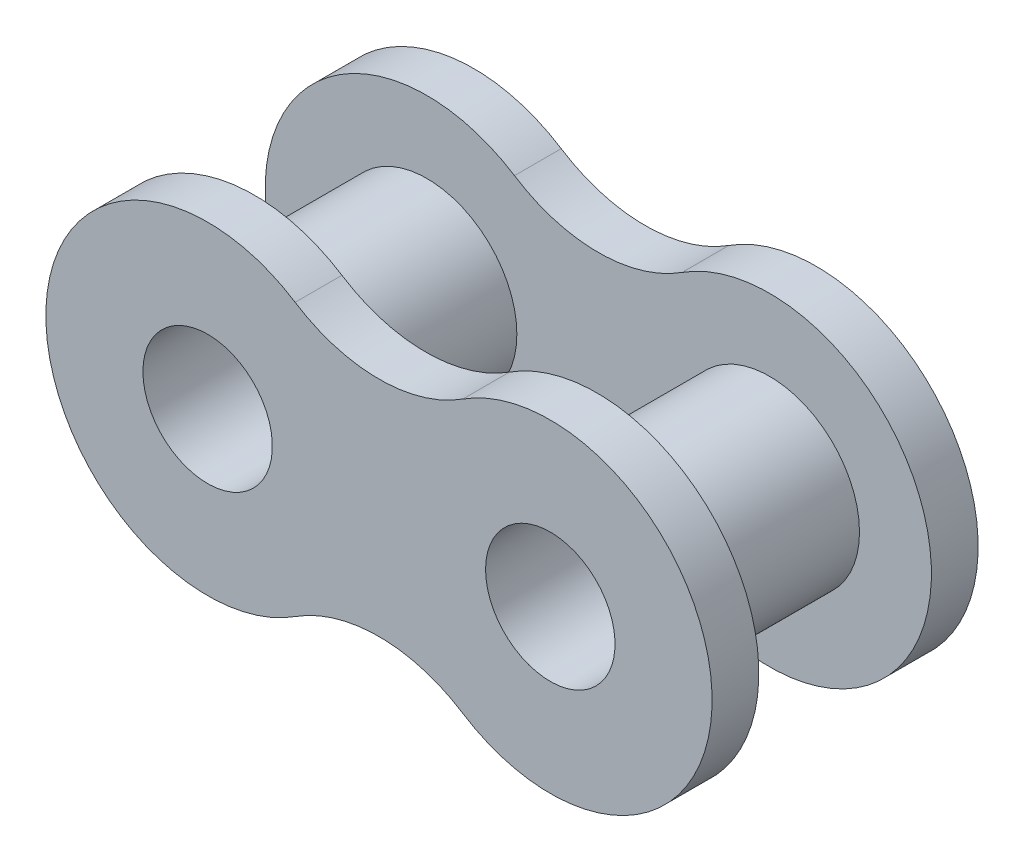
SolidWorks part; units mm, degrees
ref_plane "Alzado" through (0, 0, 0) normal (0, 0, 1) x (1, 0, 0)
ref_plane "Planta" through (0, 0, 0) normal (0, 1, 0) x (1, 0, 0)
ref_plane "Vista lateral" through (0, 0, 0) normal (1, 0, 0) x (0, 0, -1)
sketch "Sketch1" plane through (0, 0, 0) normal (0, 0, 1) x (1, 0, 0)
  line L0 (-9.265, 0) -> (9.265, 0) construction
  line L1 (0, 3.1) -> (0, -3.1) construction
  arc A0 (-2.3308, 3.7848) -> (-2.3308, -3.7848) centre (-4.765, 0) ccw
  arc A1 (-2.3308, 3.7848) -> (2.3308, 3.7848) centre (0, 7.409) ccw
  arc A2 (-2.3308, -3.7848) -> (2.3308, -3.7848) centre (0, -7.409) cw
  arc A3 (2.3308, 3.7848) -> (2.3308, -3.7848) centre (4.765, 0) cw
  point P4 (0, 0)
  point P10 (0, 0)
  dimension "D1" = 9
  dimension "D3" = 9.53
  dimension "D2" = 6.2
extrude "Boss-Extrude1" add sketch "Sketch1" along normal blind 1.3
sketch "Sketch2" plane through (0, 0, 1.3) normal (0, 0, 1) x (1, 0, 0)
  circle A0 centre (-4.765, 0) radius 2.5
  circle A1 centre (4.765, 0) radius 2.5
  circle A2 centre (-4.765, 0) radius 1.8
  circle A3 centre (4.765, 0) radius 1.8
  dimension "D1" = 5
  dimension "D2" = 3.6
ref_plane "Plane1" through (0, 0, 3.7) normal (0, 0, -1) x (-1, 0, 0)
extrude "Boss-Extrude2" add sketch "Sketch2" along normal blind 5
mirror "Mirror5" about plane through (0, 0, 3.7) normal (0, 0, -1) of "Boss-Extrude1"
sketch "Sketch4" plane through (0, 0, 3.7) normal (0, 0, -1) x (-1, 0, 0)
  circle A0 centre (-4.765, 0) radius 1.8 construction
  circle A1 centre (4.765, 0) radius 1.8 construction
  circle A2 centre (-4.765, 0) radius 1.8
  circle A3 centre (4.765, 0) radius 1.8
extrude "Cut-Extrude1" cut sketch "Sketch4" against normal through all both and the other way through all
